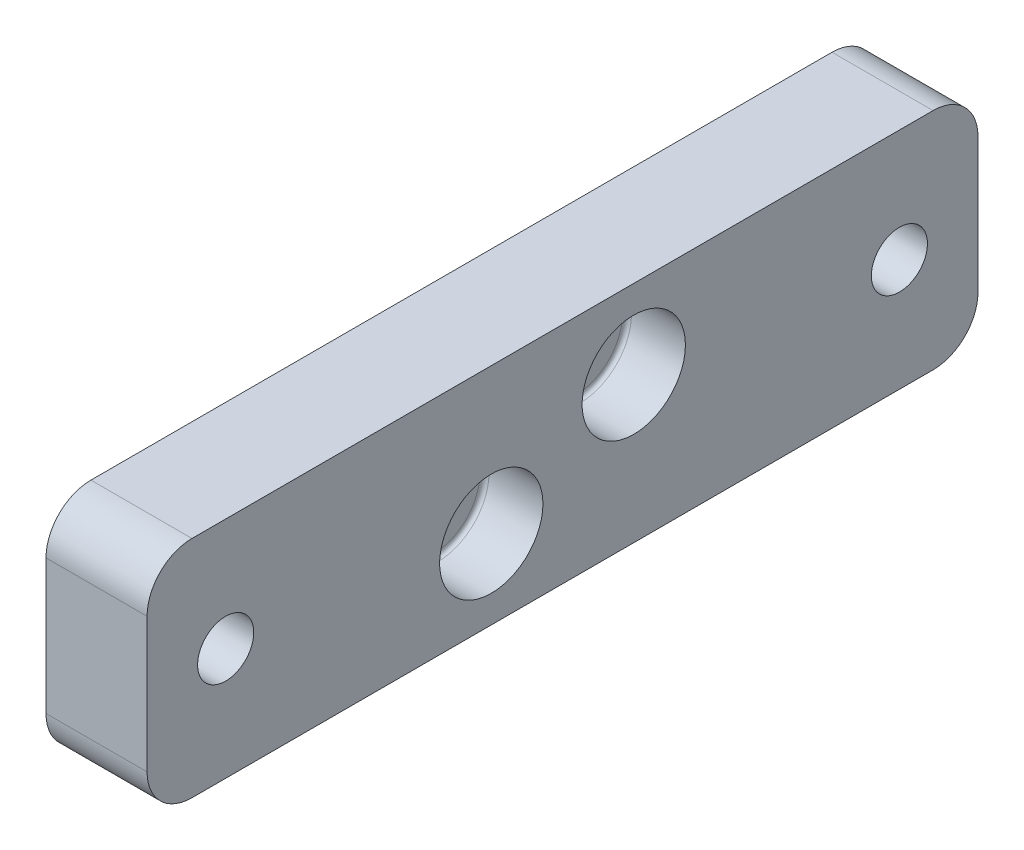
SolidWorks part; units mm, degrees
material "PLA"
ref_plane "Front Plane" through (0, 0, 0) normal (0, 0, 1) x (1, 0, 0)
ref_plane "Top Plane" through (0, 0, 0) normal (0, 1, 0) x (1, 0, 0)
ref_plane "Right Plane" through (0, 0, 0) normal (1, 0, 0) x (0, 0, -1)
sketch "Sketch1" plane through (0, 0, 0) normal (1, 0, 0) x (0, 0, -1)
  line L0 (0, 0) -> (0, 28686.8703) construction
  line L1 (0, 0) -> (28686.8703, 0) construction
  line L2 (23.495, 6.35) -> (-23.495, 6.35)
  line L3 (-23.495, 6.35) -> (-23.495, -6.35)
  line L4 (23.495, -6.35) -> (-23.495, -6.35)
  line L5 (23.495, 6.35) -> (23.495, -6.35)
  line L8 (0, 0) -> (-4.0285, -1.8785) construction
  line L9 (4.0285, 1.8785) -> (0, 0) construction
  circle A0 centre (-19.05, 0) radius 1.5875
  circle A1 centre (19.05, 0) radius 1.5875
  circle A2 centre (-4.0285, -1.8785) radius 1.6129
  circle A3 centre (4.0285, 1.8785) radius 1.6129
  point P5 (23.495, 0)
  point P9 (-23.495, 0)
  point P11 (0, -6.35)
  point P12 (0, 6.35)
  dimension "D3" = 3.175
  dimension "D5" = 3.2258
  dimension "D1" = 46.99
  dimension "D2" = 12.7
  dimension "D4" = 38.1
  dimension "D7" = 4.445
  dimension "D8" = 4.445
  dimension "D9" = 25
  dimension "D10" = 25
extrude "Boss-Extrude1" add sketch "Sketch1" along normal blind 5.715
sketch "Sketch2" plane through (5.715, 0, 0) normal (1, 0, 0) x (0, 0, -1)
  circle A0 centre (-4.0285, -1.8785) radius 2.921
  circle A1 centre (4.0285, 1.8785) radius 2.921
  dimension "D1" = 5.842
extrude "Cut-Extrude1" cut sketch "Sketch2" against normal blind 3.302
fillet "Fillet1" radius 2.54 4 edges at (2.8575, -6.35, -23.495) (2.8575, 6.35, -23.495) (2.8575, -6.35, 23.495) (2.8575, 6.35, 23.495)
fillet "Fillet2" radius 0.254 2 edges at (2.413, -1.8785, 1.1075) (2.413, 1.8785, -6.9495)
